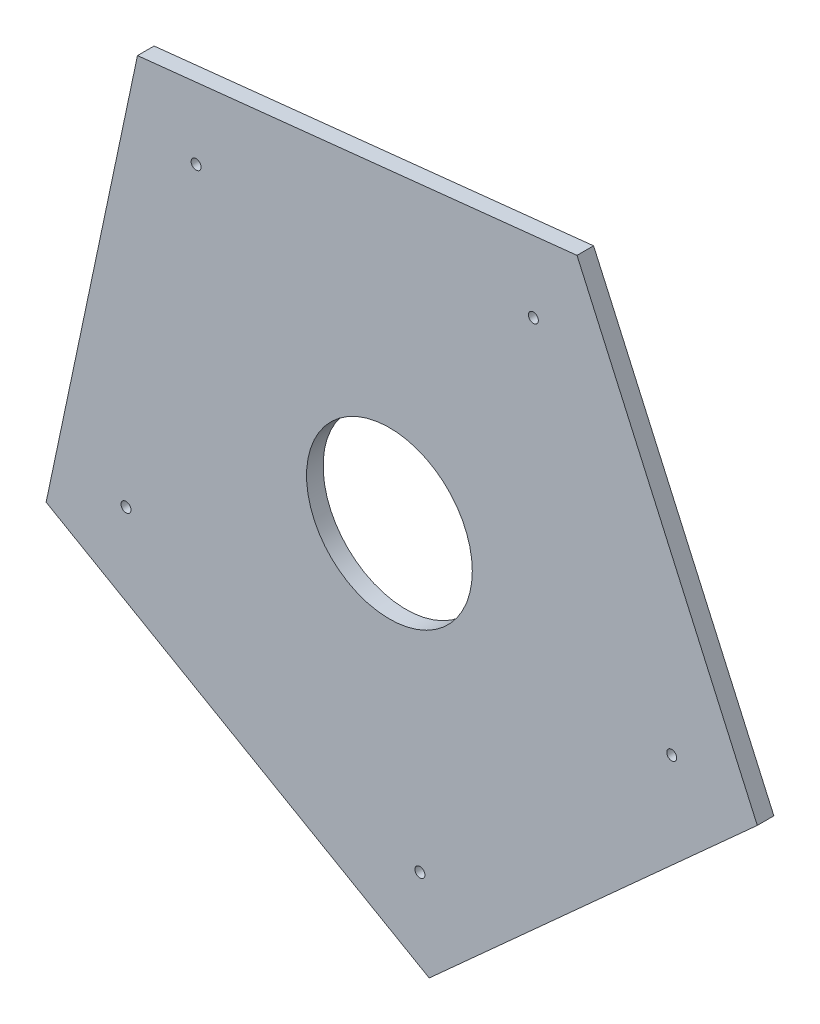
SolidWorks part; units mm, degrees
ref_plane "Front Plane" through (0, 0, 0) normal (0, 0, 1) x (1, 0, 0)
ref_plane "Top Plane" through (0, 0, 0) normal (0, 1, 0) x (1, 0, 0)
ref_plane "Right Plane" through (0, 0, 0) normal (1, 0, 0) x (0, 0, -1)
sketch "Sketch1" plane through (0, 0, 0) normal (0, 0, 1) x (1, 0, 0)
  line L1 (-62.1335, -27.7582) -> (7.1993, -67.6702)
  line L2 (7.1993, -67.6702) -> (66.5829, -14.0643)
  line L3 (66.5829, -14.0643) -> (33.9512, 58.978)
  line L4 (33.9512, 58.978) -> (-45.5999, 50.5147)
  line L5 (-45.5999, 50.5147) -> (-62.1335, -27.7582)
  circle A0 centre (0, 0) radius 55.0553 construction
  dimension "D1" = 80
extrude "Boss-Extrude1" add sketch "Sketch1" along normal blind 3 contours L4 L5 L1 L2 L3
sketch "Sketch3" plane through (0, 0, 3) normal (0, 0, 1) x (1, 0, 0)
  circle A0 centre (0, 0) radius 15
  point P29 (0, 0)
extrude "Cut-Extrude1" cut sketch "Sketch3" against normal blind 3 contours A0
sketch "Sketch4" plane through (0, 0, 0) normal (0, 0, -1) x (-1, 0, 0)
  line L0 (0, 0) -> (62.1335, -27.7582) construction
  line L1 (0, 0) -> (47.6783, -21.3004)
  circle A0 centre (47.6783, -21.3004) radius 0.9
  dimension "D1" = 52.22
extrude "Cut-Extrude2" cut sketch "Sketch4" against normal blind 3 contours A0
pattern_circular "CirPattern1" count 5 over 360 about axis through (0, 0, 0) along (0, 0, 1) of "Cut-Extrude2"
